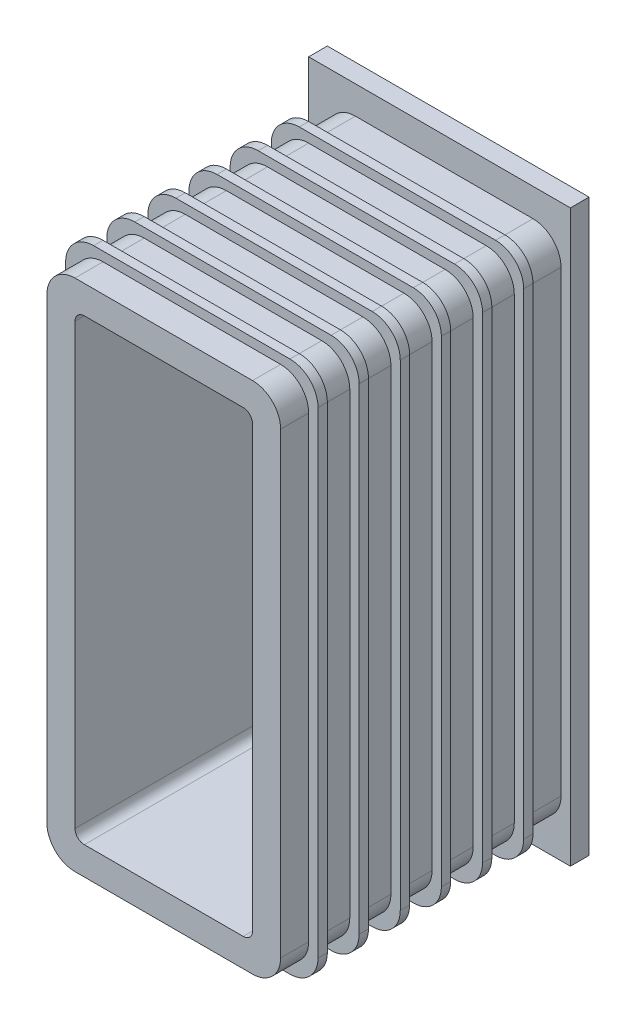
SolidWorks part; units mm, degrees
ref_plane "Front Plane" through (0, 0, 0) normal (0, 0, 1) x (1, 0, 0)
ref_plane "Top Plane" through (0, 0, 0) normal (0, 1, 0) x (1, 0, 0)
ref_plane "Right Plane" through (0, 0, 0) normal (1, 0, 0) x (0, 0, -1)
sketch "Sketch2" plane through (0, 0, 0) normal (0, 0, 1) x (1, 0, 0)
  line L1 (-25, 112.5) -> (25, 112.5)
  line L2 (-25, 112.5) -> (-25, -112.5)
  line L3 (-25, -112.5) -> (25, -112.5)
  line L4 (25, 112.5) -> (25, -112.5)
  line L5 (-15, 102.5) -> (15, 102.5)
  line L6 (-15, 102.5) -> (-15, -102.5)
  line L7 (-15, -102.5) -> (15, -102.5)
  line L8 (15, 102.5) -> (15, -102.5)
  dimension "D1" = 25
  dimension "D2" = 112.5
  dimension "D3" = 50
  dimension "D4" = 225
  dimension "D5" = 10
  dimension "D6" = 10
  dimension "D7" = 10
  dimension "D8" = 10
extrude "Boss-Extrude1" add sketch "Sketch2" against normal blind 25
sketch "Sketch3" plane through (0, 0, 0) normal (0, 0, 1) x (1, 0, 0)
  line L0 (15, 102.5) -> (-15, 102.5) construction
  line L1 (-55, 152.5) -> (85, 152.5)
  line L2 (-55, 152.5) -> (-55, -152.5)
  line L3 (-55, -152.5) -> (85, -152.5)
  line L4 (85, 152.5) -> (85, -152.5)
  line L5 (-15, 102.5) -> (15, 102.5)
  line L6 (-15, 102.5) -> (-15, -102.5)
  line L7 (-15, -102.5) -> (15, -102.5)
  line L8 (15, 102.5) -> (15, -102.5)
  line L9 (-15, 102.5) -> (-15, -102.5) construction
  line L10 (15, -102.5) -> (15, 102.5) construction
  line L11 (-15, -102.5) -> (15, -102.5) construction
  line L12 (25, 112.5) -> (-25, 112.5) construction
  line L13 (25, -112.5) -> (25, 112.5) construction
  line L14 (-25, -112.5) -> (25, -112.5) construction
  line L15 (-25, 112.5) -> (-25, -112.5) construction
  dimension "D1" = 40
  dimension "D2" = 60
  dimension "D3" = 40
  dimension "D4" = 30
extrude "Boss-Extrude2" add sketch "Sketch3" along normal blind 10
sketch "Sketch4" plane through (0, 0, 10) normal (0, 0, 1) x (1, 0, 0)
  line L0 (85, 152.5) -> (-55, 152.5) construction
  line L1 (-30, 137.5) -> (65, 137.5)
  line L2 (-45, 122.5) -> (-45, -122.5)
  line L3 (-30, -137.5) -> (65, -137.5)
  line L4 (80, 122.5) -> (80, -122.5)
  line L5 (85, -152.5) -> (85, 152.5) construction
  line L6 (-55, 152.5) -> (-55, -152.5) construction
  line L7 (-55, -152.5) -> (85, -152.5) construction
  line L9 (-25, 122.5) -> (60, 122.5)
  line L10 (-30, 117.5) -> (-30, -117.5)
  line L11 (-25, -122.5) -> (60, -122.5)
  line L12 (65, 117.5) -> (65, -117.5)
  arc A0 (-45, -122.5) -> (-30, -137.5) centre (-30, -122.5) ccw
  arc A1 (65, -137.5) -> (80, -122.5) centre (65, -122.5) ccw
  arc A2 (65, 137.5) -> (80, 122.5) centre (65, 122.5) cw
  arc A3 (-30, 137.5) -> (-45, 122.5) centre (-30, 122.5) ccw
  arc A4 (-30, -117.5) -> (-25, -122.5) centre (-25, -117.5) ccw
  arc A5 (60, -122.5) -> (65, -117.5) centre (60, -117.5) ccw
  arc A6 (60, 122.5) -> (65, 117.5) centre (60, 117.5) cw
  arc A7 (-25, 122.5) -> (-30, 117.5) centre (-25, 117.5) ccw
  dimension "D5" = 15
  dimension "D6" = 5
  dimension "D1" = 15
  dimension "D2" = 5
  dimension "D3" = 10
  dimension "D4" = 15
extrude "Boss-Extrude3" add sketch "Sketch4" along normal blind 150
sketch "Sketch5" plane through (0, 0, 10) normal (0, 0, 1) x (1, 0, 0)
  line L0 (65, 137.5) -> (-30, 137.5) construction
  line L1 (-35, 142.5) -> (70, 142.5)
  line L2 (-50, 127.5) -> (-50, -127.5)
  line L3 (-35, -142.5) -> (70, -142.5)
  line L4 (85, 127.5) -> (85, -127.5)
  line L5 (-45, 122.5) -> (-45, -122.5) construction
  line L6 (-30, -137.5) -> (65, -137.5) construction
  line L7 (80, -122.5) -> (80, 122.5) construction
  line L8 (80, -122.5) -> (80, 122.5) construction
  line L9 (-30, 137.5) -> (65, 137.5)
  line L10 (-45, 122.5) -> (-45, -122.5)
  line L11 (-30, -137.5) -> (65, -137.5)
  line L12 (80, 122.5) -> (80, -122.5)
  arc A1 (-50, -127.5) -> (-35, -142.5) centre (-35, -127.5) ccw
  arc A2 (70, -142.5) -> (85, -127.5) centre (70, -127.5) ccw
  arc A3 (70, 142.5) -> (85, 127.5) centre (70, 127.5) cw
  arc A4 (-35, 142.5) -> (-50, 127.5) centre (-35, 127.5) ccw
  arc A5 (-30, 137.5) -> (-45, 122.5) centre (-30, 122.5) ccw
  arc A6 (65, 137.5) -> (80, 122.5) centre (65, 122.5) cw
  arc A7 (65, -137.5) -> (80, -122.5) centre (65, -122.5) ccw
  arc A8 (-45, -122.5) -> (-30, -137.5) centre (-30, -122.5) ccw
  dimension "D3" = 5
  dimension "D5" = 15
  dimension "D6" = 15
  dimension "D1" = 5
  dimension "D2" = 5
  dimension "D4" = 5
extrude "Boss-Extrude4" add sketch "Sketch5" along normal blind 5 from offset 20
pattern_linear "LPattern1" count 6 spacing 22 along (0, 0, 1) of "Boss-Extrude4"
